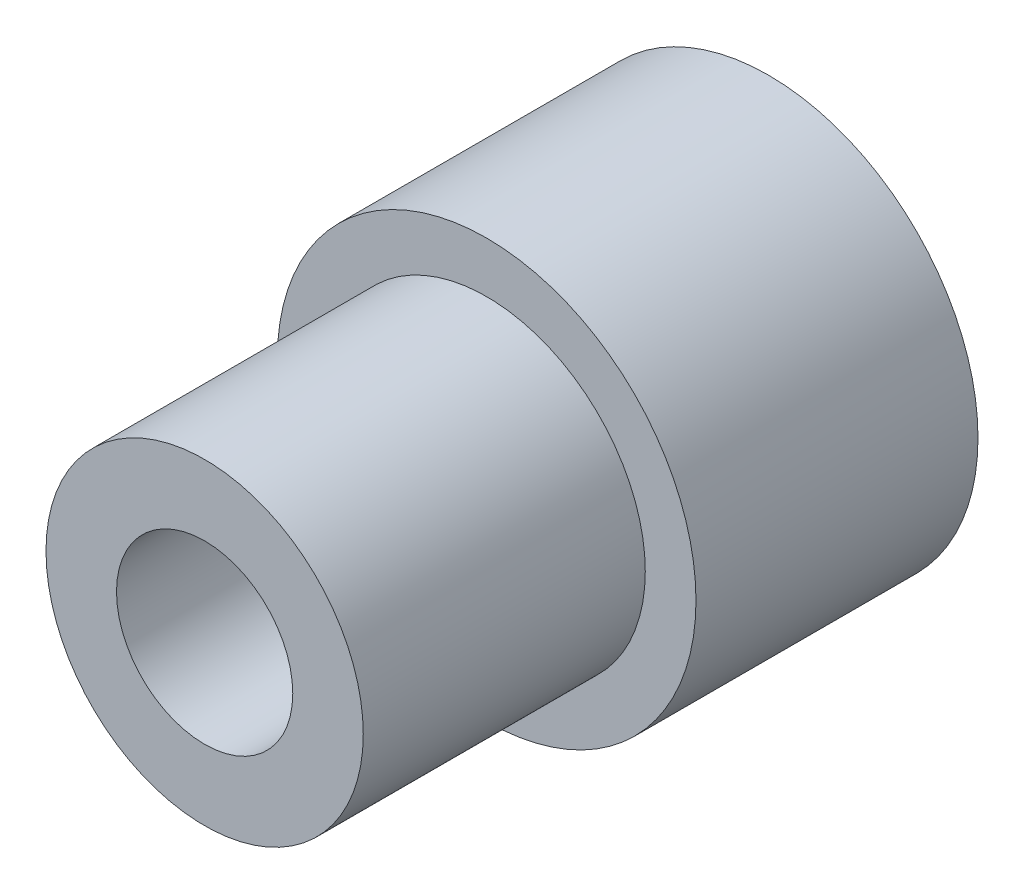
SolidWorks part; units mm, degrees
ref_plane "Front Plane" through (0, 0, 0) normal (0, 0, 1) x (1, 0, 0)
ref_plane "Top Plane" through (0, 0, 0) normal (0, 1, 0) x (1, 0, 0)
ref_plane "Right Plane" through (0, 0, 0) normal (1, 0, 0) x (0, 0, -1)
sketch "Sketch1" plane through (0, 0, 0) normal (0, 0, 1) x (1, 0, 0)
  circle A0 centre (0, 0) radius 2.5006
  circle A1 centre (0, 0) radius 3.7706
  dimension "D1" = 5.0013
  dimension "D2" = 1.27
extrude "Boss-Extrude1" add sketch "Sketch1" along normal blind 5.08
sketch "Sketch2" plane through (0, 0, 5.08) normal (0, 0, 1) x (1, 0, 0)
  circle A0 centre (0, 0) radius 2.8575
  circle A1 centre (0, 0) radius 1.5875
  dimension "D1" = 3.175
  dimension "D2" = 1.27
extrude "Boss-Extrude2" add sketch "Sketch2" along normal blind 5.08
